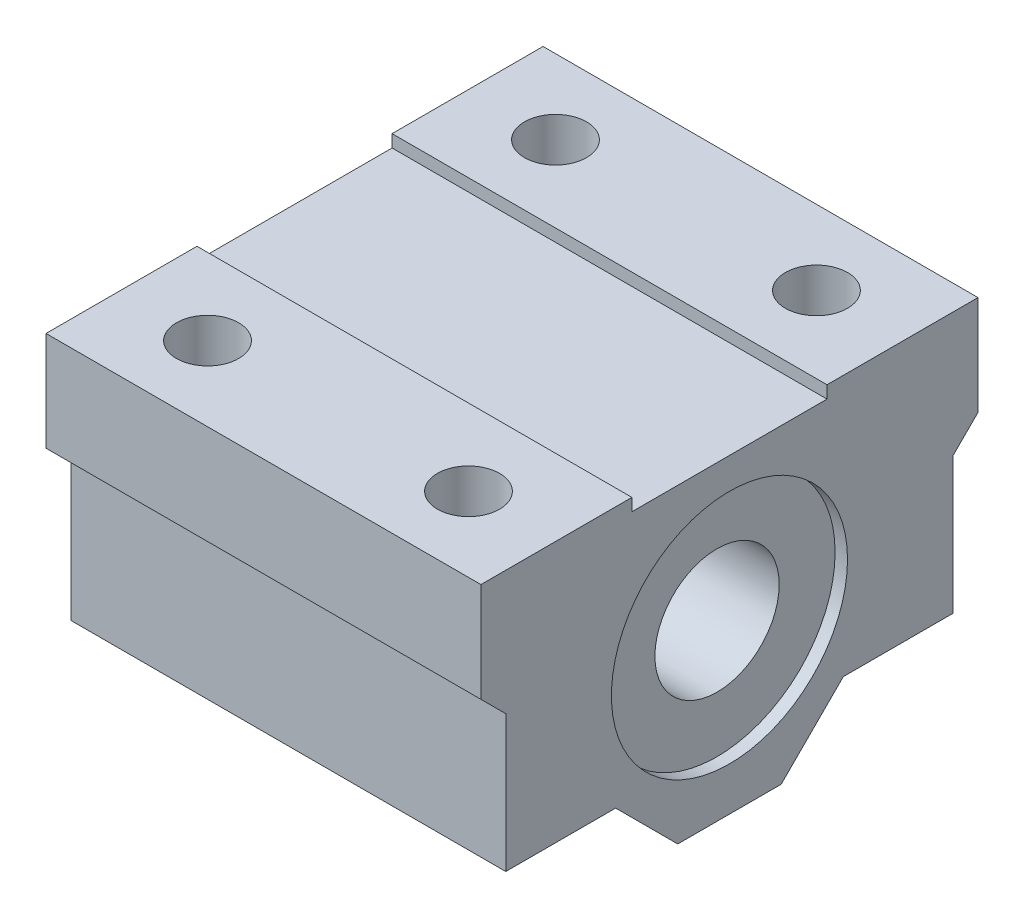
SolidWorks part; units mm, degrees
ref_plane "Front Plane" through (0, 0, 0) normal (0, 0, 1) x (1, 0, 0)
ref_plane "Top Plane" through (0, 0, 0) normal (0, 1, 0) x (1, 0, 0)
ref_plane "Right Plane" through (0, 0, 0) normal (1, 0, 0) x (0, 0, -1)
sketch "Sketch1" plane through (0, 0, 0) normal (1, 0, 0) x (0, 0, -1)
  line L0 (-20, 26) -> (-7.85, 26)
  line L1 (0, -14.5279) -> (0, 39.1137) construction
  line L2 (-20, 26) -> (-20, 18)
  line L3 (-20, 18) -> (-18, 16)
  line L4 (-18, 16) -> (-18, 5)
  line L5 (-18, 5) -> (-9.1611, 5)
  line L6 (-9.1611, 5) -> (-4.1611, 0)
  line L7 (-4.1611, 0) -> (4.1611, 0)
  line L8 (20, 26) -> (20, 18)
  line L9 (20, 18) -> (18, 16)
  line L10 (18, 16) -> (18, 5)
  line L11 (18, 5) -> (9.1611, 5)
  line L12 (9.1611, 5) -> (4.1611, 0)
  line L13 (7.85, 26) -> (7.85, 25)
  line L14 (14, 31.2174) -> (14, 14.8601)
  line L15 (-7.85, 25) -> (7.85, 25)
  line L16 (7.85, 26) -> (20, 26)
  line L18 (-7.85, 26) -> (-7.85, 25)
  circle A0 centre (0, 13) radius 5
  point P16 (0, 0)
  dimension "D10" = 10
  dimension "D1" = 40
  dimension "D2" = 1
  dimension "D3" = 26
  dimension "D4" = 8
  dimension "D5" = 21
  dimension "D6" = 13
  dimension "D7" = 2
  dimension "D8" = 5
  dimension "D9" = 6
extrude "Boss-Extrude1" add sketch "Sketch1" along normal mid plane 35
ref_plane "Plane1" through (0, 18, 0) normal (0, 1, 0) x (-1, 0, 0)
sketch "Sketch3" plane through (0, 18, 0) normal (0, 1, 0) x (-1, 0, 0)
  circle A0 centre (-10.5, 14) radius 2.5
  circle A1 centre (10.5, 14) radius 2.5
  circle A2 centre (-10.5, -14) radius 2.5
  circle A3 centre (10.5, -14) radius 2.5
  dimension "D5" = 5
extrude "Cut-Extrude1" cut sketch "Sketch3" along normal blind 16
sketch "Sketch4" plane through (0, 18, 0) normal (0, 1, 0) x (-1, 0, 0)
  circle A0 centre (-10.5, 14) radius 2.15
  circle A1 centre (10.5, 14) radius 2.15
  circle A2 centre (10.5, -14) radius 2.15
  circle A3 centre (-10.5, -14) radius 2.15
  dimension "D1" = 4.3
extrude "Cut-Extrude2" cut sketch "Sketch4" against normal blind 26
sketch "Sketch9" plane through (17.5, 0, 0) normal (1, 0, 0) x (0, 0, -1)
  circle A0 centre (0, 13) radius 9.5
  dimension "D1" = 19
extrude "Cut-Extrude5" cut sketch "Sketch9" against normal blind 1
mirror "Mirror4" about plane through (0, 0, 0) normal (1, 0, 0) of "Cut-Extrude5"
